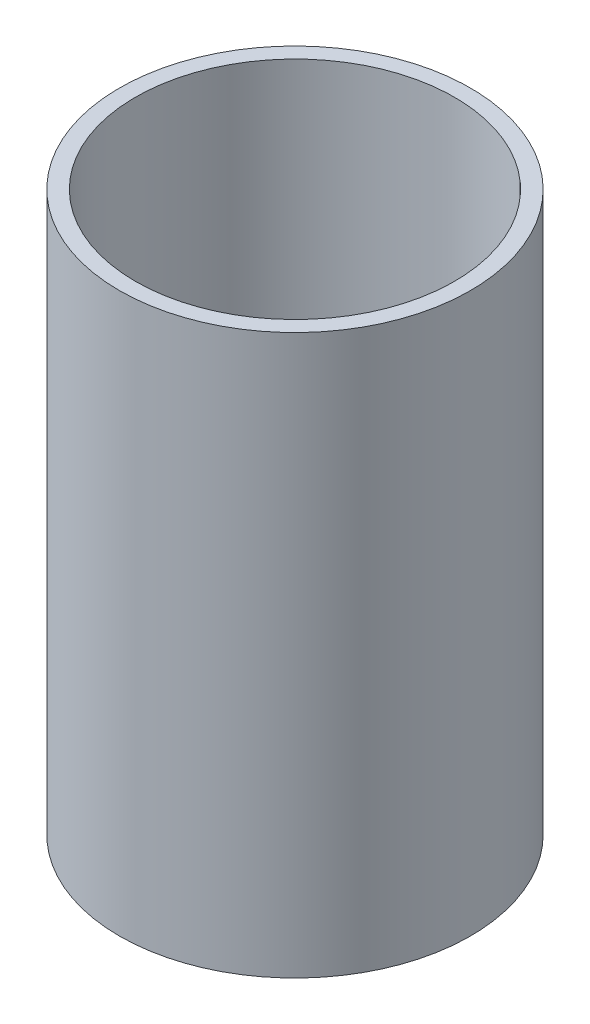
SolidWorks part; units mm, degrees
ref_plane "Front Plane" through (0, 0, 0) normal (0, 0, 1) x (1, 0, 0)
ref_plane "Top Plane" through (0, 0, 0) normal (0, 1, 0) x (1, 0, 0)
ref_plane "Right Plane" through (0, 0, 0) normal (1, 0, 0) x (0, 0, -1)
sketch "Sketch1" plane through (0, 0, 0) normal (0, 1, 0) x (1, 0, 0)
  circle A0 centre (0, 0) radius 63.5
  circle A1 centre (0, 0) radius 69.85
  dimension "D1" = 127
  dimension "D2" = 6.35
extrude "Boss-Extrude1" add sketch "Sketch1" along normal blind 222.5012
equation "\"height\"= \"volume\" / ( ( 3.14159265 / 4 ) * \"id\" ^ 2 )"
equation "\"id\"= 5in"
equation "\"volume\"= 172"
equation "\"D1@Boss-Extrude1\"=\"height\""
